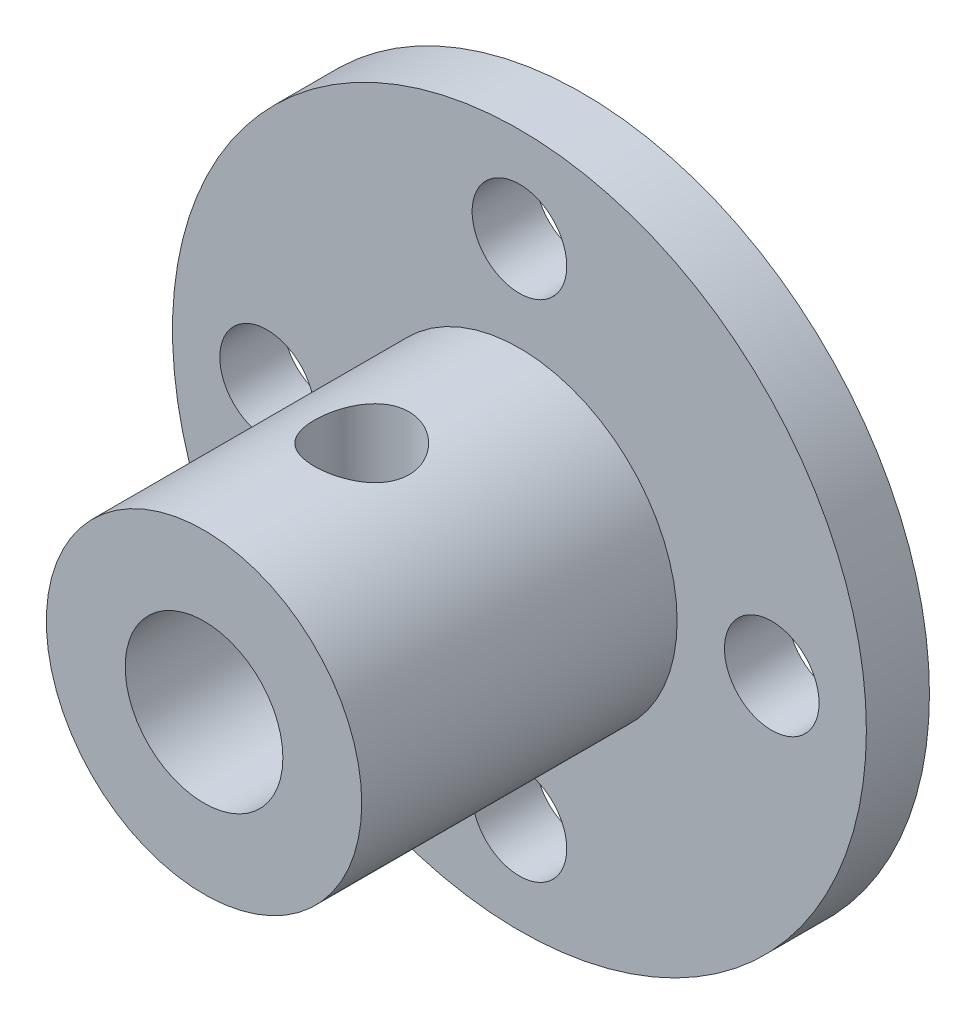
SolidWorks part; units mm, degrees
ref_plane "Спереди" through (0, 0, 0) normal (0, 0, 1) x (1, 0, 0)
ref_plane "Сверху" through (0, 0, 0) normal (0, 1, 0) x (1, 0, 0)
ref_plane "Справа" through (0, 0, 0) normal (1, 0, 0) x (0, 0, -1)
sketch "Эскиз1" plane through (0, 0, 0) normal (0, 0, 1) x (1, 0, 0)
  circle A0 centre (0, 0) radius 11
  circle A1 centre (-8, 0) radius 1.5
  circle A2 centre (0, 8) radius 1.5
  circle A3 centre (8, 0) radius 1.5
  circle A4 centre (0, -8) radius 1.5
  circle A5 centre (0, 0) radius 2.5
  point P14 (0, 0)
  dimension "D1" = 22
  dimension "D2" = 3
  dimension "D5" = 5
  dimension "D4" = 16
  dimension "D3" = 4
extrude "Бобышка-Вытянуть1" add sketch "Эскиз1" along normal blind 2
sketch "Эскиз2" plane through (0, 0, 2) normal (0, 0, 1) x (1, 0, 0)
  circle A0 centre (0, 0) radius 2.5 construction
  circle A1 centre (0, 0) radius 2.5
  circle A2 centre (0, 0) radius 5
  dimension "D1" = 10
extrude "Бобышка-Вытянуть2" add sketch "Эскиз2" along normal blind 10
sketch "Эскиз3" plane through (0, 0, 0) normal (0, 1, 0) x (1, 0, 0)
  line L0 (-5, -2) -> (-5, -12) construction
  circle A0 centre (0, -7) radius 1.5
  point P5 (-5, -7)
  dimension "D1" = 3
extrude "Вырез-Вытянуть1" cut sketch "Эскиз3" against normal through all both and the other way through all
